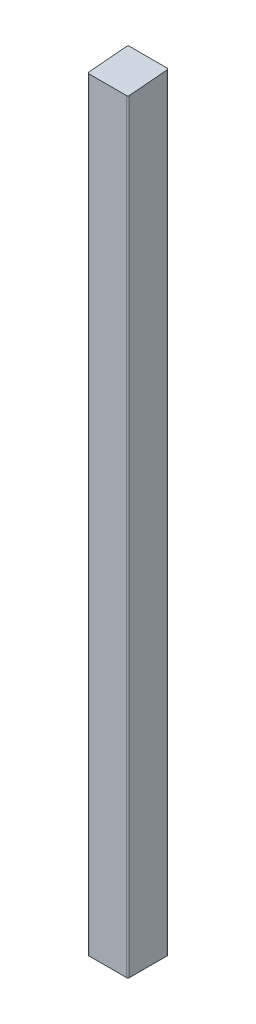
SolidWorks part; units mm, degrees
material "Pine"
ref_plane "Front Plane" through (0, 0, 0) normal (0, 0, 1) x (1, 0, 0)
ref_plane "Top Plane" through (0, 0, 0) normal (0, 1, 0) x (1, 0, 0)
ref_plane "Right Plane" through (0, 0, 0) normal (1, 0, 0) x (0, 0, -1)
sketch "Sketch1" plane through (0, 0, 0) normal (1, 0, 0) x (0, 0, -1)
  line L0 (0, 0) -> (0, 1673.225)
  line L1 (0, 1673.225) -> (88.9, 1681.0027)
  line L2 (88.9, 1681.0027) -> (88.9, 0)
  line L3 (88.9, 0) -> (0, 0)
  dimension "D1" = 1673.225
  dimension "D2" = 88.9
  dimension "D3" = 85
  dimension "D4" = 1681.0027
extrude "Boss-Extrude1" add sketch "Sketch1" along normal mid plane 88.9
fillet "Fillet1" radius 3.175 4 edges at (-44.45, 840.5014, -88.9) (44.45, 840.5014, -88.9) (-44.45, 836.6125, 0) (44.45, 836.6125, 0)
sketch "Sketch2" plane through (44.45, 0, 0) normal (1, 0, 0) x (0, 0, -1)
  line L0 (44.45, 996.95) -> (44.45, 844.55) construction
  line L1 (3.175, 0) -> (85.725, 0) construction
  line L2 (44.45, 527.05) -> (44.45, 127) construction
  line L3 (44.45, 1635.125) -> (44.45, 1330.325) construction
  point P5 (44.45, 0)
  point P9 (0, 1673.225)
  dimension "D1" = 152.4
  dimension "D2" = 996.95
  dimension "D3" = 400.05
  dimension "D4" = 127
  dimension "D5" = 38.1
  dimension "D6" = 304.8
